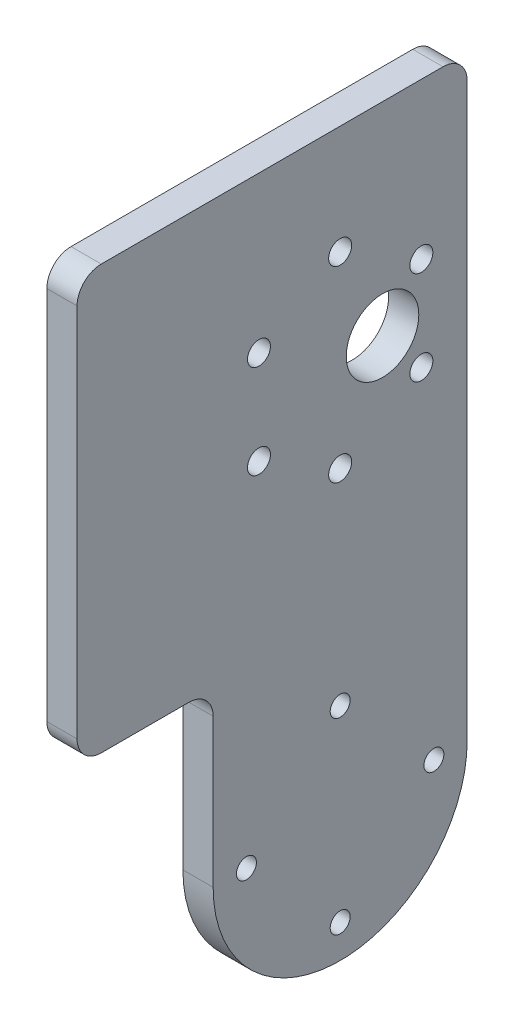
SolidWorks part; units mm, degrees
ref_plane "Front Plane" through (0, 0, 0) normal (1, 0, 0) x (0, 1, 0)
ref_plane "Top Plane" through (0, 0, 0) normal (0, 0, 1) x (0, 1, 0)
ref_plane "Right Plane" through (0, 0, 0) normal (0, 1, 0) x (-1, 0, 0)
sketch "Sketch1" plane through (0, 0, 0) normal (1, 0, 0) x (0, 1, 0)
  line L1 (0, 0) -> (94.5, 0)
  line L2 (28.5, 46) -> (28.5, 60.5)
  line L3 (32.5, 64.5) -> (94.5, 64.5)
  line L4 (98.5, 4) -> (98.5, 60.5)
  line L5 (-163.3002, 39.5) -> (10.3636, 39.5) construction
  line L6 (-28.2563, 2.5) -> (49.027, 2.5) construction
  line L7 (-18.5, 8.1559) -> (-18.5, 18.2674) construction
  line L8 (18.5, -9.0658) -> (18.5, 49990.9342) construction
  line L9 (0, -63.9378) -> (0, -168.3827) construction
  line L10 (0, 42) -> (24.5, 42)
  line L12 (46.5, 7.1832) -> (46.5, 17.2948) construction
  line L14 (83.5, -10.0384) -> (83.5, 49989.9616) construction
  line L15 (65, -64.9105) -> (65, -169.3554) construction
  arc A1 (94.5, 0) -> (98.5, 4) centre (94.5, 4) ccw
  arc A2 (94.5, 64.5) -> (98.5, 60.5) centre (94.5, 60.5) cw
  arc A3 (28.5, 60.5) -> (32.5, 64.5) centre (32.5, 60.5) cw
  circle A5 centre (0, 21) radius 18.5 construction
  circle A6 centre (0, 21) radius 15.5 construction
  circle A7 centre (-15.5, 21) radius 1.65
  arc A13 (0, 42) -> (0, 0) centre (0, 21) ccw
  arc A14 (24.5, 42) -> (28.5, 46) centre (24.5, 46) ccw
  circle A15 centre (0, 21) radius 21 construction
  circle A20 centre (65, 21) radius 15.5 construction
  circle A21 centre (49.5, 21) radius 1.9
  circle A22 centre (65, 21) radius 18.5 construction
  circle A23 centre (65, 14) radius 6
  circle A24 centre (57.25, 34.4234) radius 1.9
  circle A25 centre (72.75, 34.4234) radius 1.9
  circle A26 centre (80.5, 21) radius 1.9
  circle A27 centre (72.75, 7.5766) radius 1.9
  circle A28 centre (57.25, 7.5766) radius 1.9
  circle A29 centre (0, 36.5) radius 1.65
  circle A30 centre (15.5, 21) radius 1.65
  circle A31 centre (0, 5.5) radius 1.65
  point P5 (-11.2755, 30.5839)
  point P7 (0, 0)
  dimension "D6" = 31
  dimension "D7" = 37
  dimension "D5" = 3.3
  dimension "D14" = 4
  dimension "D15" = 37
  dimension "D16" = 31
  dimension "D17" = 3.8
  dimension "D18" = 12
  dimension "D4" = 70
  dimension "D11" = 10
  dimension "D12" = 5
  dimension "D2" = 25
  dimension "D3" = 64.5
  dimension "D13" = 2.5
  dimension "D19" = 7
  dimension "D21" = 15
  dimension "D20" = 6
  dimension "D8" = 4
extrude "Boss-Extrude1" add sketch "Sketch1" along normal blind 5
equation "\"ThighLength\"= 200"
equation "\"BearingBore\"=4"
equation "\"MinShinWidth\"= 20"
equation "\"HipBore\"=27"
equation "\"ShinThickness\"=10"
equation "\"ThighThickness\"=20"
equation "\"MaxBending\"=135"
equation "\"MaxStretchingAngle\"= 140"
equation "\"ThighJointDistance\"=157.485"
equation "\"PivotDistance\"=40"
equation "\"ShinLength\"=100"
equation "\"BearingDiameter\"= 10"
equation "\"MotorDriverLength\"= 60mm"
equation "\"MotorLength\"= 60"
equation "\"MotorDriverWidth\"=45"
equation "\"MotorWidth\"= 37"
equation "\"InnerWallThickness\"=3"
equation "\"BatteryWidth\"= 60"
equation "\"OuterWallThickness\" = 5"
equation "\"CompartmentHeight\"=37"
equation "\"CompartmentWidth\"= \"MotorDriverLength\""
equation "\"MotorDiameter\"=37"
equation "\"BatteryHeight\"=24.2019"
equation "\"MotorDriverHeight\"=20"
equation "\"CircuitHeight\"=30"
equation "\"FanThickness\"= 10"
equation "\"FanHeight\"=50"
equation "\"MotorShaftHole\"=12"
equation "\"ThighThickness\"=30"
equation "\"D4@Sketch1\"=\"MotorDriverLength\" + \"OuterWallThickness\"*2"
equation "\"D1@Boss-Extrude1\"=\"OuterWallThickness\""
equation "\"D12@Sketch1\"=\"OuterWallThickness\""
equation "\"D2@Sketch1\"=\"OuterWallThickness\"+\"MotorDriverHeight\""
equation "\"D13@Sketch1\"=\"OuterWallThickness\"/2"
equation "\"D21@Sketch1\"=\"OuterWallThickness\"+\"FanThickness\""
